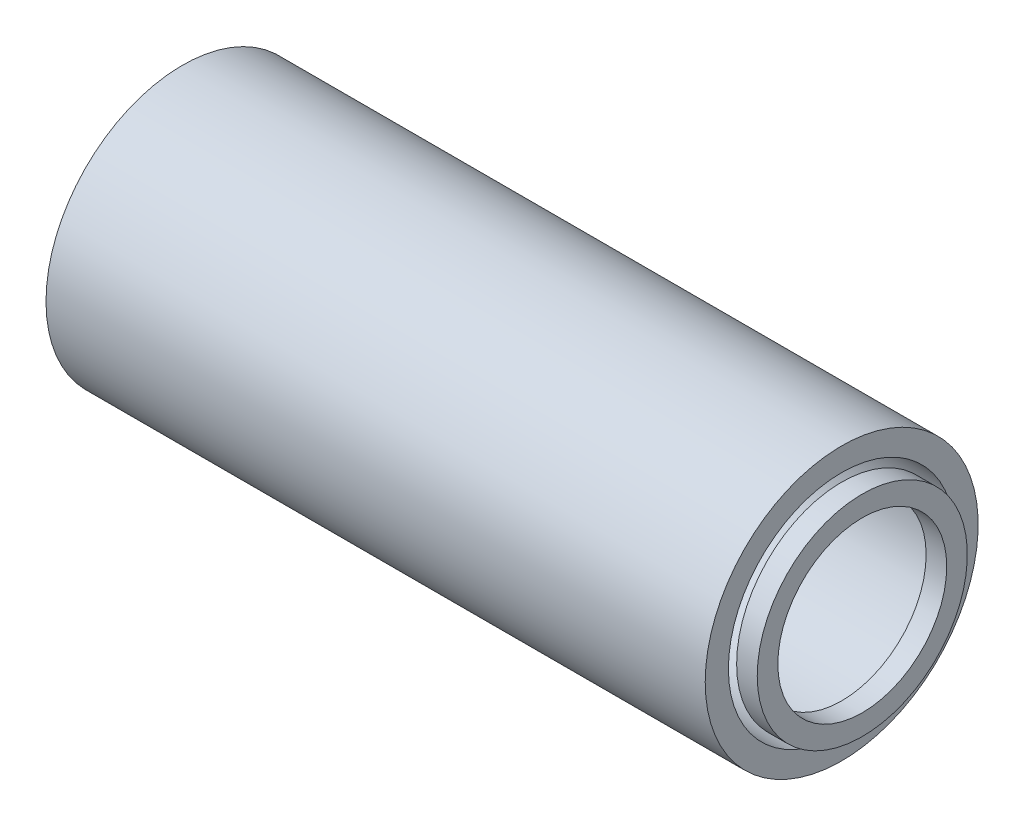
SolidWorks part; units mm, degrees
ref_plane "Front Plane" through (0, 0, 0) normal (0, 0, 1) x (1, 0, 0)
ref_plane "Top Plane" through (0, 0, 0) normal (0, 1, 0) x (1, 0, 0)
ref_plane "Right Plane" through (0, 0, 0) normal (1, 0, 0) x (0, 0, -1)
sketch "Sketch1" plane through (0, 0, 0) normal (0, 0, 1) x (1, 0, 0)
  line L0 (-50.8, 0) -> (50.8, 0) construction
  line L1 (-50.8, 17.4625) -> (50.8, 17.4625)
  line L2 (-50.8, 17.4625) -> (-50.8, 21.0344)
  line L3 (-50.8, 21.0344) -> (50.8, 21.0344)
  line L4 (50.8, 17.4625) -> (50.8, 21.0344)
  dimension "D1" = 101.6
  dimension "D2" = 34.925
  dimension "D3" = 42.0688
revolve "Revolve1" add sketch "Sketch1" angle 360 about L0
sketch "Sketch2" plane through (0, 0, 0) normal (0, 0, 1) x (1, 0, 0)
  line L0 (35.8775, 9.525) -> (42.2275, 9.525)
  line L1 (42.2275, 9.525) -> (42.2275, 13.0175)
  line L2 (53.975, 16.1925) -> (50.8, 16.1925)
  line L3 (50.8, 16.1925) -> (50.8, -21.0344)
  line L4 (50.8, -21.0344) -> (39.6875, -21.0344)
  line L5 (39.0525, -21.6694) -> (39.6875, -21.0344)
  line L6 (39.0525, -21.6694) -> (35.8775, -21.6694)
  line L7 (35.8775, -21.6694) -> (35.8775, 9.525)
  line L11 (50.8, 17.4625) -> (-50.8, 17.4625) construction
  line L12 (50.8, 0) -> (152.7592, 0) construction
  line L13 (50.8, -17.4625) -> (50.8, 17.4625) construction
  line L14 (42.2275, 13.0175) -> (53.975, 13.0175)
  line L15 (53.975, 13.0175) -> (53.975, 16.1925)
  dimension "D1" = 1.27
  dimension "D2" = 3.175
  dimension "D3" = 11.1125
  dimension "D4" = 0.635
  dimension "D5" = 45
  dimension "D6" = 3.175
  dimension "D7" = 19.05
  dimension "D8" = 3.175
  dimension "D9" = 6.35
revolve "Revolve2" add sketch "Sketch2" angle 360 about L12
mirror "Mirror2" about plane through (0, 0, 0) normal (1, 0, 0) of bodies 102
